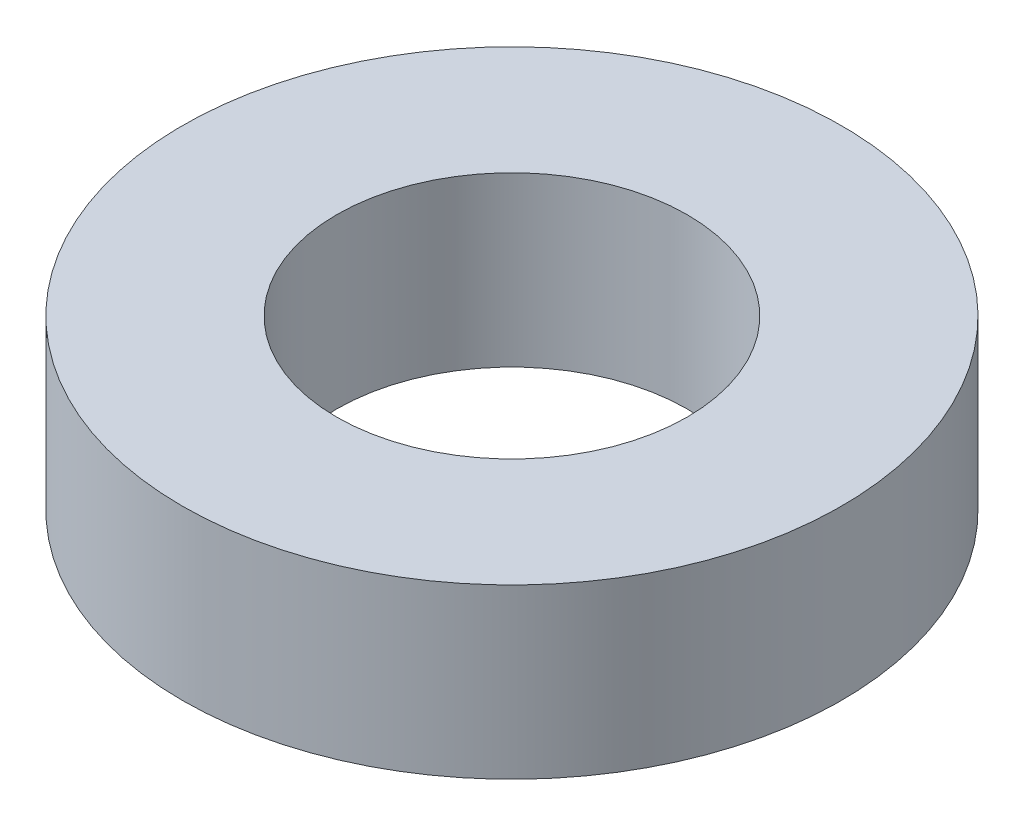
SolidWorks part; units mm, degrees
ref_plane "Front Plane" through (0, 0, 0) normal (0, 0, 1) x (1, 0, 0)
ref_plane "Top Plane" through (0, 0, 0) normal (0, 1, 0) x (1, 0, 0)
ref_plane "Right Plane" through (0, 0, 0) normal (1, 0, 0) x (0, 0, -1)
sketch "Sketch1" plane through (0, 0, 0) normal (0, 1, 0) x (1, 0, 0)
  circle A0 centre (0, 0) radius 23.5
  circle A1 centre (0, 0) radius 12.5
  dimension "D1" = 47
  dimension "D2" = 25
extrude "Boss-Extrude1" add sketch "Sketch1" along normal blind 12
